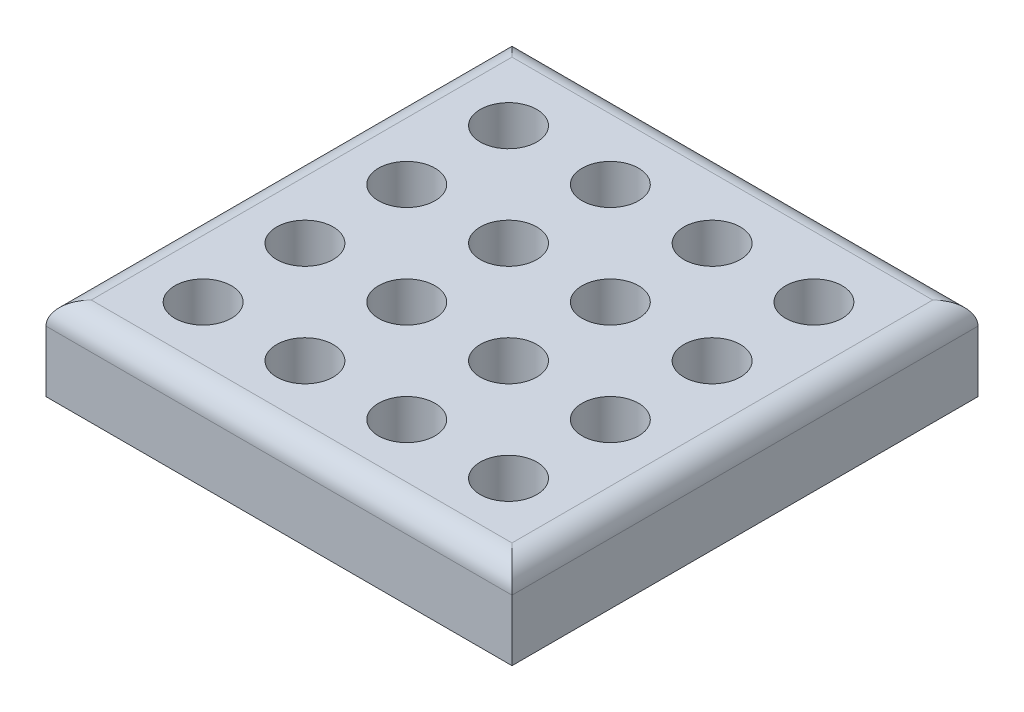
SolidWorks part; units mm, degrees
ref_plane "Front Plane" through (0, 0, 0) normal (0, 0, 1) x (1, 0, 0)
ref_plane "Top Plane" through (0, 0, 0) normal (0, 1, 0) x (1, 0, 0)
ref_plane "Right Plane" through (0, 0, 0) normal (1, 0, 0) x (0, 0, -1)
sketch "Sketch1" plane through (0, 0, 0) normal (0, 1, 0) x (1, 0, 0)
  line L1 (0, 0) -> (206, 0)
  line L2 (0, 0) -> (0, 206)
  line L3 (0, 206) -> (206, 206)
  line L4 (206, 0) -> (206, 206)
  dimension "D1" = 206
  dimension "D2" = 206
extrude "Boss-Extrude1" add sketch "Sketch1" along normal blind 37
sketch "Sketch2" plane through (0, 37, 0) normal (0, 1, 0) x (1, 0, 0)
  line L0 (35.5, 168.9652) -> (80.5, 168.9652) construction
  line L1 (206, 206) -> (0, 206) construction
  line L2 (125.5, 168.9652) -> (170.5, 168.9652) construction
  line L3 (80.5, 168.9652) -> (125.5, 168.9652) construction
  line L4 (103, 213.3576) -> (103, -10.2258) construction
  line L5 (0, 206) -> (0, 0) construction
  line L6 (206, 0) -> (206, 206) construction
  circle A3 centre (80.5, 168.9652) radius 12.5
  circle A4 centre (35.5, 168.9652) radius 12.5
  circle A5 centre (125.5, 168.9652) radius 12.5
  circle A6 centre (170.5, 168.9652) radius 12.5
  dimension "D1" = 45
  dimension "D2" = 45
  dimension "D3" = 45
extrude "Cut-Extrude1" cut sketch "Sketch2" against normal blind 30
pattern_linear "LPattern1" count 4 spacing 45 along (0, 0, 1) of "Cut-Extrude1"
fillet "Fillet2" radius 10 4 edges at (103, 37, 0) (206, 37, -103) (103, 37, -206) (0, 37, -103)
